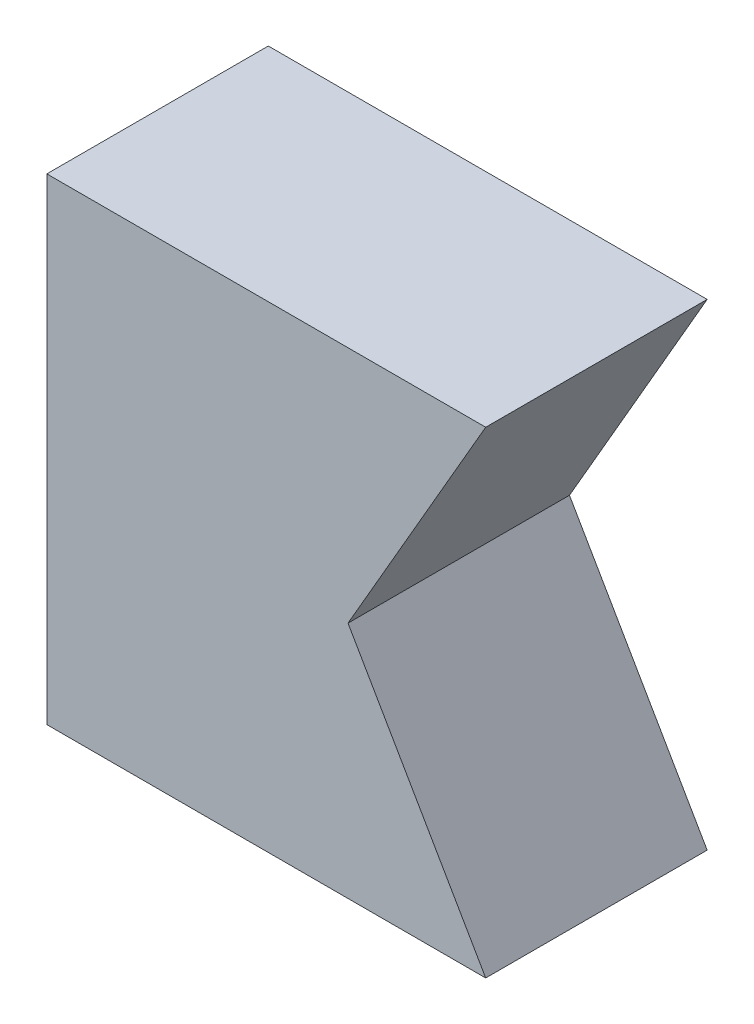
SolidWorks part; units mm, degrees
ref_plane "Alzado" through (0, 0, 0) normal (0, 0, 1) x (1, 0, 0)
ref_plane "Planta" through (0, 0, 0) normal (0, 1, 0) x (1, 0, 0)
ref_plane "Vista lateral" through (0, 0, 0) normal (1, 0, 0) x (0, 0, -1)
sketch "Croquis1" plane through (0, 0, 0) normal (1, 0, 0) x (0, 0, -1)
  line L3 (-24, 5) -> (15, 5)
  line L4 (-25, 4) -> (-25, -4)
  line L5 (-24, -5) -> (15, -5)
  line L6 (15, 5) -> (15, -5)
  arc A2 (-25, -4) -> (-24, -5) centre (-24, -4) ccw
  arc A3 (-24, 5) -> (-25, 4) centre (-24, 4) ccw
  circle A4 centre (-22, 0) radius 1.5
  point P0 (0, 0)
  point P2 (15, 0)
  dimension "D3" = 1
  dimension "D4" = 3
  dimension "D5" = 3
  dimension "D1" = 10
  dimension "D2" = 25
  dimension "D6" = 15
extrude "Saliente-Extruir1" add sketch "Croquis1" along normal mid plane 14
sketch "Croquis2" plane through (0, 0, 0) normal (0, 0, 1) x (1, 0, 0)
  circle A0 centre (0, 0) radius 1.5
  dimension "D1" = 3
extrude "Cortar-Extruir1" cut sketch "Croquis2" against normal through all and the other way blind 10
sketch "Croquis3" plane through (0, 0, 0) normal (0, 1, 0) x (1, 0, 0)
  line L0 (7, -24) -> (-7, -24) construction
  line L1 (-3, -18) -> (3, -18)
  line L2 (-3, -18) -> (-3, -25)
  line L3 (-3, -25) -> (3, -25)
  line L4 (3, -18) -> (3, -25)
  line L5 (7, -25) -> (-7, -25) construction
  point P6 (0, -24)
  point P7 (0, -25)
  point P8 (0, -18)
  dimension "D1" = 7
  dimension "D2" = 6
extrude "Cortar-Extruir2" cut sketch "Croquis3" against normal through all both and the other way through all
sketch "Croquis4" plane through (0, 0, 0) normal (0, 0, 1) x (1, 0, 0)
  line L1 (1.7321, 3) -> (-1.7321, 3)
  line L2 (-1.7321, 3) -> (-3.4641, 0)
  line L3 (-3.4641, 0) -> (-1.7321, -3)
  line L4 (-1.7321, -3) -> (1.7321, -3)
  line L5 (1.7321, -3) -> (3.4641, 0)
  line L6 (3.4641, 0) -> (1.7321, 3)
  circle A0 centre (0, 0) radius 3 construction
  dimension "D1" = 6
extrude "Cortar-Extruir3" cut sketch "Croquis4" against normal mid plane 3
sketch "Croquis5" plane through (0, 0, 0) normal (1, 0, 0) x (0, 0, -1)
  line L1 (-1.5, 3) -> (1.5, 3)
  line L2 (-1.5, 3) -> (-1.5, -3)
  line L3 (-1.5, -3) -> (1.5, -3)
  line L4 (1.5, 3) -> (1.5, -3)
extrude "Cortar-Extruir4" cut sketch "Croquis5" against normal through all flip side to cut
sketch "Croquis6" plane through (-7, 0, 0) normal (-1, 0, 0) x (0, 0, 1)
  line L8 (1.3, -2.8) -> (1.3, 2.8)
  line L9 (1.3, 2.8) -> (-1.3, 2.8)
  line L10 (-1.3, 2.8) -> (-1.3, -2.8)
  line L11 (-1.3, -2.8) -> (1.3, -2.8)
  line L12 (1.3, -2.8) -> (1.3, 2.8)
  line L13 (1.3, 2.8) -> (-1.3, 2.8)
  line L14 (-1.3, 2.8) -> (-1.3, -2.8)
  line L15 (-1.3, -2.8) -> (1.3, -2.8)
  dimension "D1" = 0.2
extrude "Cortar-Extruir5" cut sketch "Croquis6" against normal through all flip side to cut
